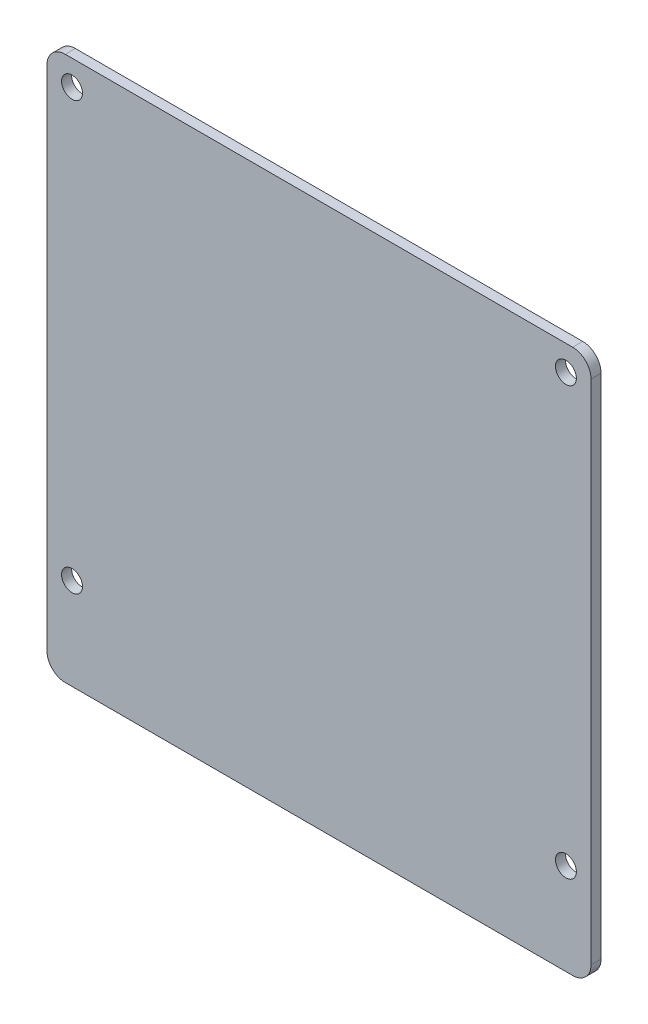
SolidWorks part; units mm, degrees
ref_plane "Front Plane" through (0, 0, 0) normal (0, 0, 1) x (1, 0, 0)
ref_plane "Top Plane" through (0, 0, 0) normal (0, 1, 0) x (1, 0, 0)
ref_plane "Right Plane" through (0, 0, 0) normal (1, 0, 0) x (0, 0, -1)
sketch "Sketch3" plane through (0, 0, 0) normal (0, 0, 1) x (1, 0, 0)
  line L0 (-32.5, 32.5) -> (32.5, -32.5) construction
  line L1 (-30.3, 32.5) -> (30.3, 32.5)
  line L2 (-32.5, 30.3) -> (-32.5, -30.3)
  line L3 (-30.3, -32.5) -> (30.3, -32.5)
  line L4 (32.5, 30.3) -> (32.5, -30.3)
  line L5 (32.5, 32.5) -> (-32.5, -32.5) construction
  line L7 (-29.5, 29.5) -> (29.5, 29.5) construction
  line L8 (-29.5, 29.5) -> (-29.5, -21.55) construction
  line L9 (-29.5, -21.55) -> (29.5, -21.55) construction
  line L10 (29.5, 29.5) -> (29.5, -21.55) construction
  arc A0 (30.3, -32.5) -> (32.5, -30.3) centre (30.3, -30.3) ccw
  arc A1 (-32.5, -30.3) -> (-30.3, -32.5) centre (-30.3, -30.3) ccw
  arc A2 (30.3, 32.5) -> (32.5, 30.3) centre (30.3, 30.3) cw
  arc A3 (-30.3, 32.5) -> (-32.5, 30.3) centre (-30.3, 30.3) ccw
  circle A4 centre (-29.5, 29.5) radius 1.25
  circle A5 centre (-29.5, -21.55) radius 1.25
  circle A6 centre (29.5, -21.55) radius 1.25
  circle A7 centre (29.5, 29.5) radius 1.25
  point P4 (0, 0)
  point P30 (0, 0)
  point P31 (0, 0)
  point P32 (0, 0)
  point P33 (0, 0)
  point P34 (0, 0)
  point P35 (0, 0)
  point P36 (0, 0)
  point P37 (0, 0)
  point P38 (0, 0)
  dimension "D3" = 2.2
  dimension "D4" = 3
  dimension "D1" = 65
  dimension "D2" = 65
  dimension "D5" = 3
  dimension "D6" = 3
  dimension "D7" = 10.95
extrude "Boss-Extrude1" add sketch "Sketch3" along normal blind 1.2
